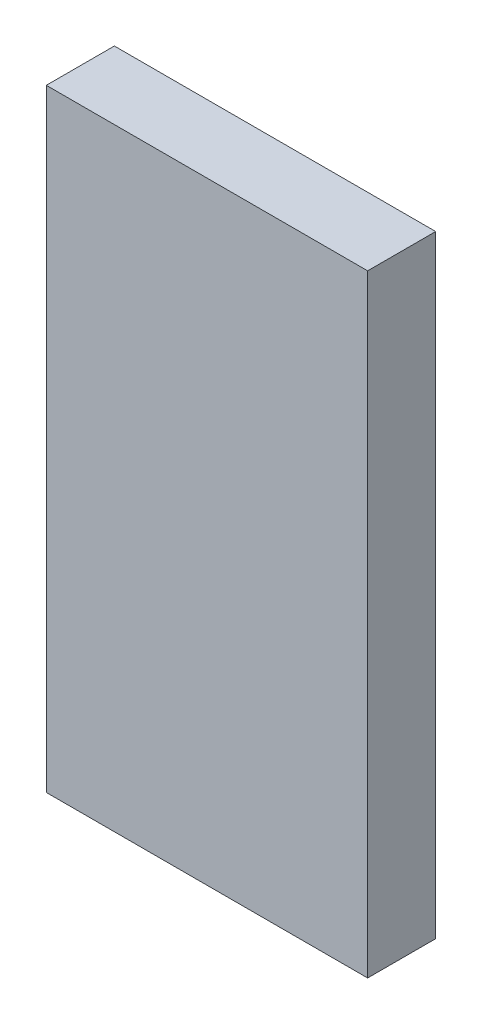
SolidWorks part; units mm, degrees
ref_plane "Спереди" through (0, 0, 0) normal (0, 0, 1) x (1, 0, 0)
ref_plane "Сверху" through (0, 0, 0) normal (0, 1, 0) x (1, 0, 0)
ref_plane "Справа" through (0, 0, 0) normal (1, 0, 0) x (0, 0, -1)
sketch "Эскиз1" plane through (0, 0, 0) normal (0, 0, 1) x (1, 0, 0)
  line L1 (0, 0) -> (85, 0)
  line L2 (0, 0) -> (0, 162)
  line L3 (0, 162) -> (85, 162)
  line L4 (85, 0) -> (85, 162)
  dimension "D1" = 85
  dimension "D2" = 162
extrude "Бобышка-Вытянуть1" add sketch "Эскиз1" along normal blind 18
